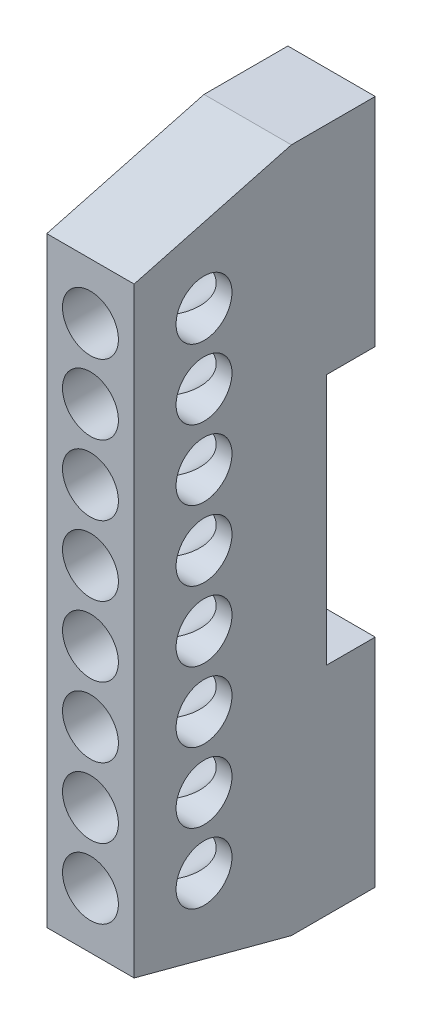
SolidWorks part; units mm, degrees
material "ПК/АБС"
ref_plane "Спереди" through (0, 0, 0) normal (0, 0, 1) x (1, 0, 0)
ref_plane "Сверху" through (0, 0, 0) normal (0, 1, 0) x (1, 0, 0)
ref_plane "Справа" through (0, 0, 0) normal (1, 0, 0) x (0, 0, -1)
sketch "Эскиз1" plane through (0, 0, 0) normal (1, 0, 0) x (0, 0, -1)
  line L0 (0, 49) -> (0, -49)
  line L1 (0, -49) -> (-12, -49)
  line L2 (-12, -49) -> (-34.5, -43)
  line L3 (-34.5, -43) -> (-34.5, 43)
  line L4 (-34.5, 43) -> (-12, 49)
  line L5 (-12, 49) -> (0, 49)
  dimension "D1" = 34.5
  dimension "D2" = 98
  dimension "D3" = 86
  dimension "D4" = 12
extrude "Бобышка-Вытянуть1" add sketch "Эскиз1" along normal mid plane 12.5
sketch "Эскиз2" plane through (0, 0, 34.5) normal (0, 0, 1) x (1, 0, 0)
  line L0 (0, 0) -> (-10.1226, 0) construction
  circle A0 centre (0, -5) radius 4
  circle A1 centre (0, -15) radius 4
  circle A2 centre (0, -25) radius 4
  circle A3 centre (0, 25) radius 4
  circle A4 centre (0, 15) radius 4
  circle A5 centre (0, 5) radius 4
  circle A6 centre (0, -35) radius 4
  circle A7 centre (0, 35) radius 4
  dimension "D2" = 8
  dimension "D3" = 10
  dimension "D4" = 5
  dimension "D1" = 4
extrude "Вырез-Вытянуть1" cut sketch "Эскиз2" against normal blind 20
sketch "Эскиз3" plane through (6.25, 0, 0) normal (1, 0, 0) x (0, 0, -1)
  line L0 (-34.5, 43) -> (-34.5, -43) construction
  circle A0 centre (-24.5, -35) radius 4
  circle A1 centre (-24.5, -25) radius 4
  circle A2 centre (-24.5, -15) radius 4
  circle A3 centre (-24.5, -5) radius 4
  circle A4 centre (-24.5, 5) radius 4
  circle A5 centre (-24.5, 15) radius 4
  circle A6 centre (-24.5, 25) radius 4
  circle A7 centre (-24.5, 35) radius 4
  dimension "D1" = 8
  dimension "D2" = 10
  dimension "D3" = 8
  dimension "D5" = 10
  dimension "D4" = 8
extrude "Вырез-Вытянуть2" cut sketch "Эскиз3" against normal through all
sketch "Эскиз4" plane through (-6.25, 0, 0) normal (-1, 0, 0) x (0, 0, 1)
  line L0 (0, -12) -> (0, 12) construction
  line L1 (0, 18) -> (7, 18)
  line L2 (0, 18) -> (0, -18)
  line L3 (0, -18) -> (7, -18)
  line L4 (7, 18) -> (7, -18)
  point P6 (0, 0)
  dimension "D1" = 36
  dimension "D2" = 7
extrude "Вырез-Вытянуть3" cut sketch "Эскиз4" against normal through all
